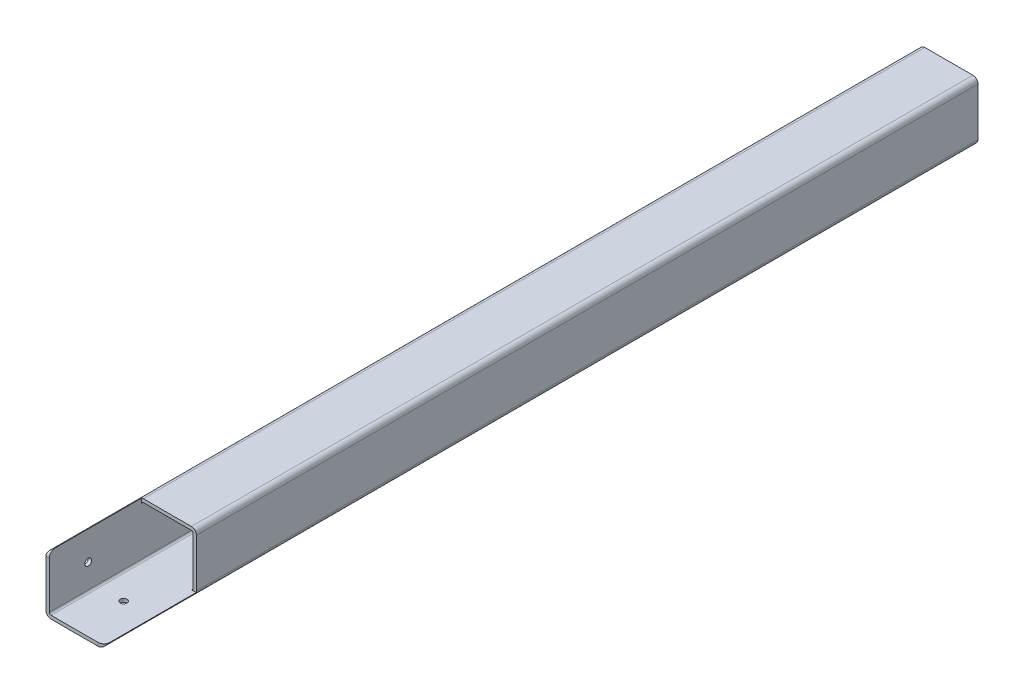
SolidWorks part; units mm, degrees
material "Ст3пс ГОСТ 380-2005"
ref_plane "Спереди" through (0, 0, 0) normal (0, 0, 1) x (1, 0, 0)
ref_plane "Сверху" through (0, 0, 0) normal (0, 1, 0) x (1, 0, 0)
ref_plane "Профиль" through (0, 0, 0) normal (1, 0, 0) x (0, 0, -1)
sketch "Эскиз1" plane through (0, 0, 0) normal (0, 0, 1) x (0, 1, 0)
  line L0 (-24.75, -26.5) -> (24.75, -26.5)
  line L1 (24.75, 30) -> (-24.75, 30)
  line L2 (-30, 24.75) -> (-30, -24.75)
  line L3 (-24.75, -30) -> (24.75, -30)
  line L4 (30, -24.75) -> (30, 24.75)
  line L5 (26.5, -24.75) -> (26.5, 24.75)
  line L6 (24.75, 26.5) -> (-24.75, 26.5)
  line L7 (-26.5, 24.75) -> (-26.5, -24.75)
  circle A0 centre (0, 0) radius 30 construction
  arc A1 (-30, -24.75) -> (-24.75, -30) centre (-24.75, -24.75) ccw
  arc A2 (24.75, -30) -> (30, -24.75) centre (24.75, -24.75) ccw
  arc A3 (24.75, 30) -> (30, 24.75) centre (24.75, 24.75) cw
  arc A4 (-24.75, 30) -> (-30, 24.75) centre (-24.75, 24.75) ccw
  arc A5 (24.75, -26.5) -> (26.5, -24.75) centre (24.75, -24.75) ccw
  arc A6 (24.75, 26.5) -> (26.5, 24.75) centre (24.75, 24.75) cw
  arc A7 (-24.75, 26.5) -> (-26.5, 24.75) centre (-24.75, 24.75) ccw
  arc A8 (-26.5, -24.75) -> (-24.75, -26.5) centre (-24.75, -24.75) ccw
  dimension "R" = 5.25
  dimension "A" = 60
  dimension "s" = 3.5
extrude "Бобышка-Вытянуть1" add sketch "Эскиз1" along normal mid plane 900
sketch "Эскиз2" plane through (0, 0, 450) normal (0, 0, 1) x (1, 0, 0)
  line L0 (-24.75, -26.5) -> (24.75, -26.5) construction
  line L1 (-26.5, 30) -> (30, 30)
  line L2 (-26.5, 30) -> (-26.5, -24.75)
  line L3 (-24.75, -26.5) -> (30, -26.5)
  line L4 (30, 30) -> (30, -26.5)
  line L5 (-26.5, 24.75) -> (-26.5, -24.75) construction
  line L6 (-26.5, -24.75) -> (-24.75, -26.5)
  line L7 (24.75, 30) -> (-24.75, 30) construction
  line L8 (30, -24.75) -> (30, 24.75) construction
extrude "Вырез-Вытянуть1" cut sketch "Эскиз2" against normal blind 95
sketch "Эскиз3" plane through (0, -30, 0) normal (0, -1, 0) x (1, 0, 0)
  line L0 (-24.75, 450) -> (24.75, 450) construction
  line L1 (-30, 450) -> (-30, -450) construction
  line L2 (23.6997, 450) -> (29.6997, 450)
  line L3 (29.6997, 450) -> (29.6997, 444)
  line L4 (29.6997, 355) -> (29.6997, 450) construction
  circle A0 centre (0, 400) radius 3.5
  arc A1 (23.6997, 450) -> (29.6997, 444) centre (23.6997, 444) cw
  dimension "D1" = 7
  dimension "D2" = 50
  dimension "D3" = 30
  dimension "D4" = 6
extrude "Вырез-Вытянуть2" cut sketch "Эскиз3" against normal through all
sketch "Эскиз4" plane through (-30, 0, 0) normal (-1, 0, 0) x (0, 0, 1)
  line L1 (450, 24.75) -> (450, -24.75) construction
  line L2 (450, -30) -> (-450, -30) construction
  line L3 (450, 29.6997) -> (355, 29.6997) construction
  line L4 (444, 29.6997) -> (450, 29.6997)
  line L5 (450, 29.6997) -> (450, 23.6997)
  circle A0 centre (410, 0) radius 3.5
  arc A1 (444, 29.6997) -> (450, 23.6997) centre (444, 23.6997) cw
  dimension "D1" = 40
  dimension "D2" = 7
  dimension "D3" = 30
  dimension "D4" = 6
extrude "Вырез-Вытянуть3" cut sketch "Эскиз4" against normal through all
